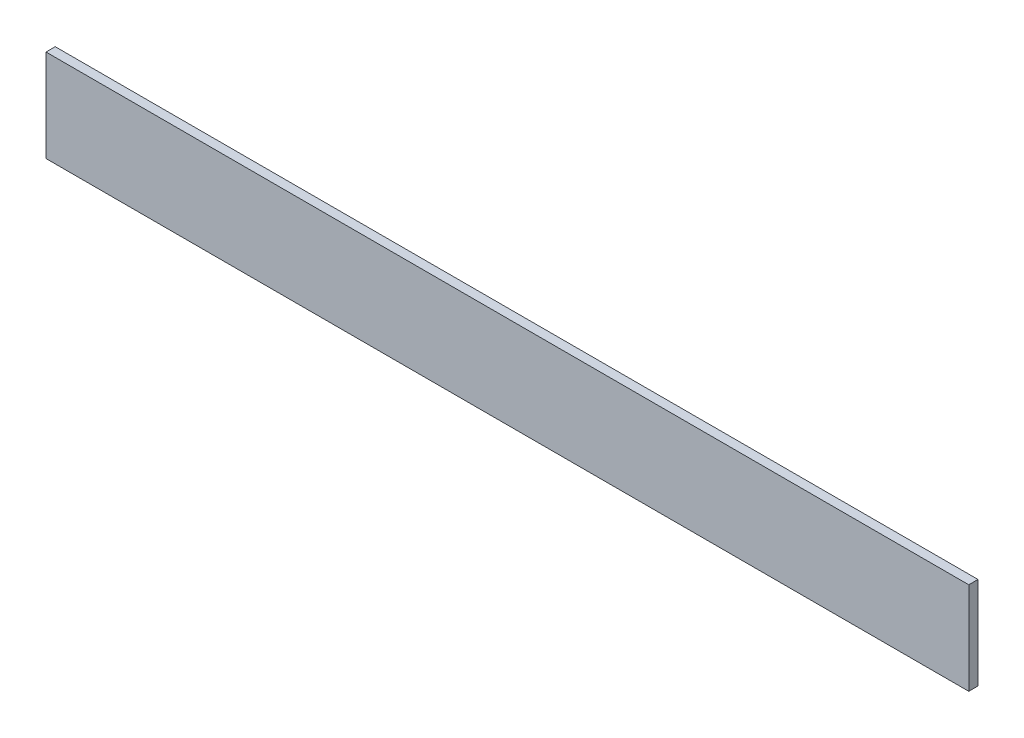
SolidWorks part; units mm, degrees
ref_plane "Front Plane" through (0, 0, 0) normal (0, 0, 1) x (1, 0, 0)
ref_plane "Top Plane" through (0, 0, 0) normal (0, 1, 0) x (1, 0, 0)
ref_plane "Right Plane" through (0, 0, 0) normal (1, 0, 0) x (0, 0, -1)
sketch "Sketch1" plane through (0, 0, 0) normal (0, 0, 1) x (1, 0, 0)
  line L1 (-198.1838, 55.8226) -> (301.8162, 55.8226)
  line L2 (-198.1838, 55.8226) -> (-198.1838, 5.8226)
  line L3 (-198.1838, 5.8226) -> (301.8162, 5.8226)
  line L4 (301.8162, 55.8226) -> (301.8162, 5.8226)
  dimension "D1" = 500
  dimension "D2" = 50
extrude "Boss-Extrude1" add sketch "Sketch1" along normal blind 5
